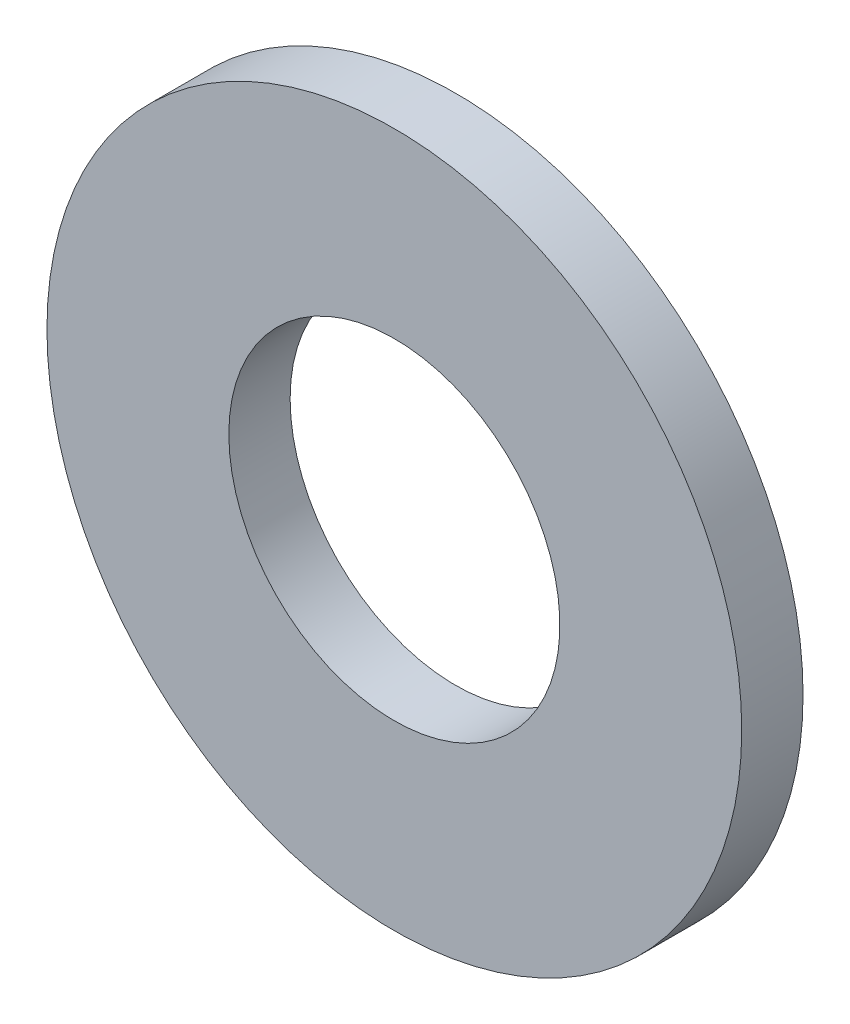
SolidWorks part; units mm, degrees
ref_plane "Front Plane" through (0, 0, 0) normal (0, 0, 1) x (1, 0, 0)
ref_plane "Top Plane" through (0, 0, 0) normal (0, 1, 0) x (1, 0, 0)
ref_plane "Right Plane" through (0, 0, 0) normal (1, 0, 0) x (0, 0, -1)
ref_plane "Plane1" through (0, 0, 0) normal (0, -1, 0) x (1, 0, 0)
sketch "Sketch1" plane through (0, 0, 0) normal (0, -1, 0) x (1, 0, 0)
  line L0 (3.4, 0) -> (3.4, 0.6)
  line L1 (3.4, 0.6) -> (1.62, 0.6)
  line L2 (1.62, 0.6) -> (1.62, 0)
  line L3 (1.62, 0) -> (3.4, 0)
  line L4 (0, 0.6) -> (0, 0) construction
revolve "Revolve1" add sketch "Sketch1" angle 360 about L4
